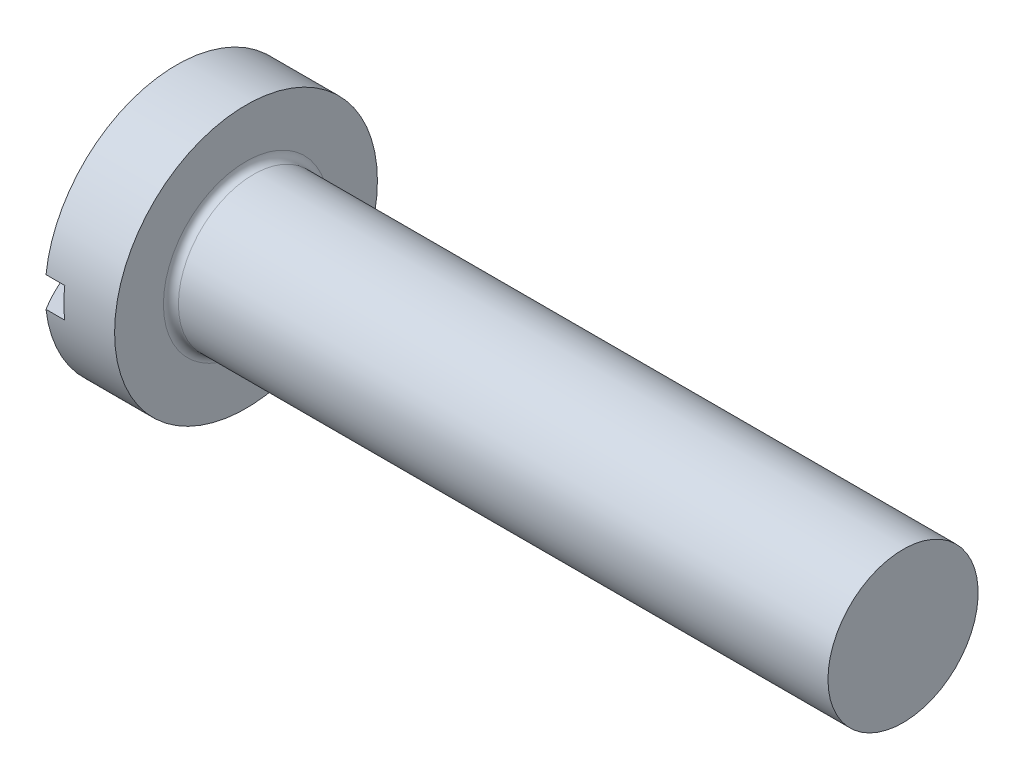
SolidWorks part; units mm, degrees
ref_plane "Plane1" through (0, 0, 0) normal (0, 0, 1) x (1, 0, 0)
ref_plane "Plane2" through (0, 0, 0) normal (0, 1, 0) x (1, 0, 0)
ref_plane "Plane3" through (0, 0, 0) normal (1, 0, 0) x (0, 0, -1)
sketch "BodySke" plane through (0, 0, 0) normal (0, 0, 1) x (1, 0, 0)
  line L0 (5.7, 4) -> (5.7, 7)
  line L1 (5.7, 7) -> (2, 7)
  line L2 (-25.4, 0) -> (127, 0) construction
  line L4 (5.7, 4) -> (40.7, 4)
  line L5 (40.7, 4) -> (40.7, 0)
  line L6 (40.7, 0) -> (0, 0)
  line L7 (5.7, -4) -> (40.7, -4) construction
  line L8 (6.95, 6.35) -> (6.95, -3.175) construction
  line L9 (10.7, 6.35) -> (10.7, -3.175) construction
  arc A0 (0, 0) -> (2, 7) centre (13.25, 0) cw
  dimension "Oval_ht" = 2
  dimension "Head_ht" = 5.7
  dimension "Diameter" = 8
  dimension "Length" = 35
  dimension "Advance" = 1.25
  dimension "Thread_nom" = 30
  dimension "Head_dia" = 14
revolve "Base-Revolve" add sketch "BodySke"
cosmetic thread "ThreadCosmetic" [suppressed]
fillet "Fillet1" radius 0.4 1 edges at (5.7, 0, 4)
sketch "Sketch2" plane through (0, 0, 0) normal (1, 0, 0) x (0, 0, -1)
  line L0 (7, -0.8) -> (7, 0.8)
  line L1 (7, 0.8) -> (-7, 0.8)
  line L2 (-7, 0.8) -> (-7, -0.8)
  line L3 (-7, -0.8) -> (7, -0.8)
  dimension "D1" = 14
  dimension "D2" = 7
  dimension "D3" = 0.8
  dimension "Slot_width" = 1.6
extrude "Slot" cut sketch "Sketch2" along normal blind 3
sketch "ThdSchSke" plane through (0, 0, 0) normal (0, 0, 1) x (1, 0, 0)
  line L0 (10.7, -3.3095) -> (10.2165, -4)
  line L1 (10.7, -3.3095) -> (11.1835, -4)
  line L2 (11.1835, -4) -> (11.1835, -5)
  line L3 (-3.175, 0) -> (5.1513, 0) construction
  line L5 (11.1835, -5) -> (10.2165, -5)
  line L6 (10.2165, -5) -> (10.2165, -4)
  dimension "Diameter" = 8
  dimension "SideAngle" = 55
  dimension "VeeAngle" = 70
  dimension "Thread_minor" = 6.619
  dimension "Overcut" = 10
  dimension "Start" = 10.7
revolve "ThreadSchematic" [suppressed] cut sketch "ThdSchSke" angle 360 about L3
pattern_linear "ThdSchPat" [suppressed]
equation "' \"Diameter@BodySke\" = 8"
equation "' \"Length@BodySke\" = 35"
equation "' \"Head_dia@BodySke\" = 14"
equation "' \"Oval_ht@BodySke\" = 2"
equation "' \"Head_ht@BodySke\" = 5.7"
equation "' \"Thread_nom@BodySke\" =  30"
equation "' \"Thread_nom@BodySke\" = 30"
equation "' \"Slot_width@Sketch2\" = 1.6"
equation "' \"Slot_depth@Slot\" = 3"
equation "' \"Thread_minor@ThreadCosmetic\" = 6.619"
equation "' \"Advance@BodySke\" = 1.25"
equation "\"D1@Sketch2\" = \"Head_dia@BodySke\""
equation "\"D2@Sketch2\" = \"D1@Sketch2\" / 2"
equation "\"D3@Sketch2\" = \"Slot_width@Sketch2\" / 2"
equation "\"Thread_length@ThreadCosmetic\" = ((sgn( (\"Length@BodySke\" - \"Advance@BodySke\" * 2 ) - \"Thread_nom@BodySke\" )-1)*( (\"Length@BodySke\" - \"Advance@BodySke\" * 2 ) - \"Thread_nom@BodySke\" ))/-2+ \"Thread_nom@BodySke\""
equation "\"Thread_minor@ThdSchSke\" = \"Thread_minor@ThreadCosmetic\""
equation "\"Diameter@ThdSchSke\" = \"Diameter@BodySke\""
equation "\"Overcut@ThdSchSke\" = \"Diameter@BodySke\" * 1.25"
equation "\"Start@ThdSchSke\" = \"Head_ht@BodySke\" + \"Length@BodySke\" - \"Thread_length@ThreadCosmetic\"  '---Non-countersunk---"
equation "\"Num_threads@ThdSchPat\" = int( \"Thread_length@ThreadCosmetic\" / \"Advance@BodySke\" + 0.999 )  + 1"
equation "\"Advance@ThdSchPat\" = \"Thread_length@ThreadCosmetic\" /  (\"Num_threads@ThdSchPat\" - 1) 'relax it"
